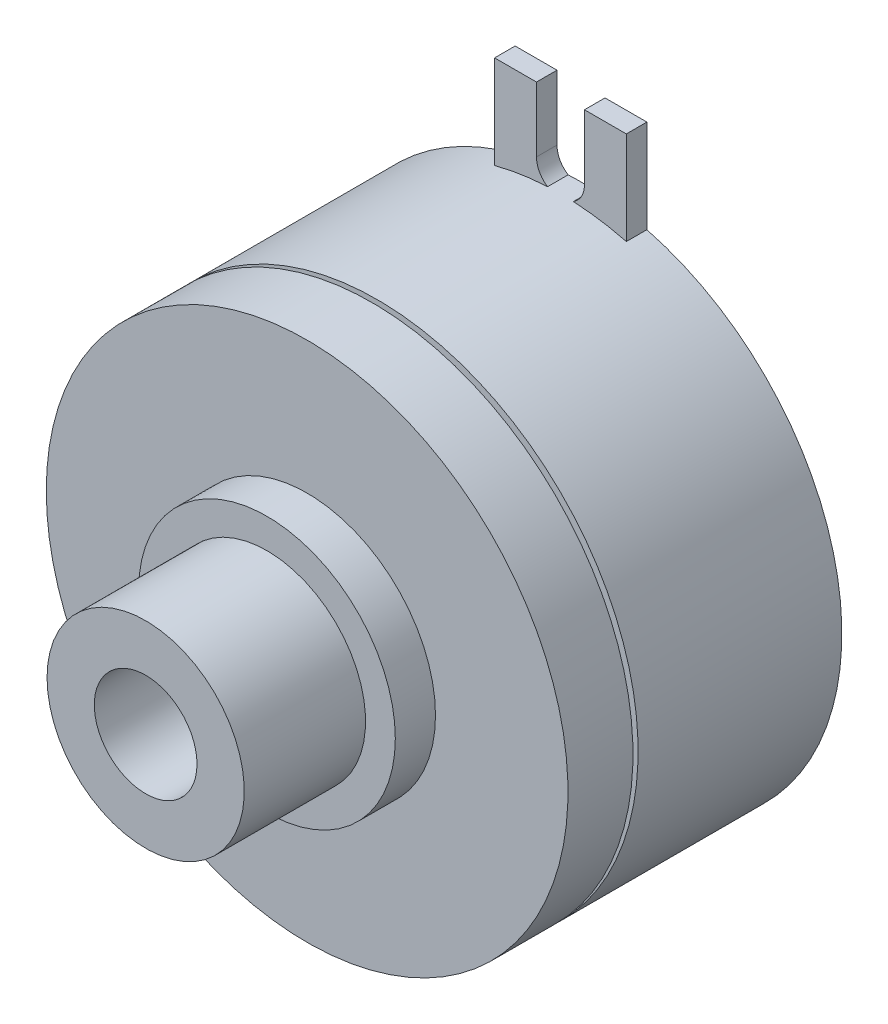
SolidWorks part; units mm, degrees
ref_plane "Front" through (0, 0, 0) normal (0, 0, 1) x (1, 0, 0)
ref_plane "Top" through (0, 0, 0) normal (0, 1, 0) x (1, 0, 0)
ref_plane "Right" through (0, 0, 0) normal (1, 0, 0) x (0, 0, -1)
sketch "Sketch1" plane through (0, 0, 0) normal (0, 0, 1) x (1, 0, 0)
  circle A0 centre (0, 0) radius 9.61
  dimension "D1" = 19.22
extrude "Boss-Extrude1" add sketch "Sketch1" along normal blind 7.087
sketch "Sketch2" plane through (0, 0, 7.087) normal (0, 0, 1) x (1, 0, 0)
  circle A0 centre (0, 0) radius 25.4
  dimension "D1" = 50.8
extrude "Boss-Extrude2" add sketch "Sketch2" along normal blind 26.67
sketch "Sketch3" plane through (0, 0, 33.757) normal (0, 0, 1) x (1, 0, 0)
  circle A0 centre (0, 0) radius 12.5
  dimension "D1" = 25
extrude "Boss-Extrude3" add sketch "Sketch3" along normal blind 3.911
sketch "Sketch4" plane through (0, 0, 37.668) normal (0, 0, 1) x (1, 0, 0)
  circle A0 centre (0, 0) radius 9.601
  dimension "D1" = 19.202
extrude "Boss-Extrude4" add sketch "Sketch4" along normal blind 11.811
sketch "Sketch6" plane through (0, 0, 7.087) normal (0, 0, -1) x (-1, 0, 0)
  line L0 (0, 36.8599) -> (0, 0) construction
  line L1 (-6.4135, 33.655) -> (-2.337, 33.655)
  line L2 (-2.337, 33.655) -> (-2.337, 27.34)
  line L4 (2.337, 27.34) -> (2.337, 33.655)
  line L5 (2.337, 33.655) -> (6.4135, 33.655)
  line L6 (6.4135, 33.655) -> (6.4135, 24.577)
  line L7 (-6.4135, 33.655) -> (-6.4135, 24.577)
  circle A0 centre (0, 0) radius 25.4 construction
  arc A1 (-2.337, 27.34) -> (2.337, 27.34) centre (0, 27.34) ccw
  circle A3 centre (0, 0) radius 9.61 construction
  circle A5 centre (0, 0) radius 25.4
  arc A6 (-6.4135, 24.577) -> (6.4135, 24.577) centre (0, 0) ccw
  dimension "D1" = 4.674
  dimension "D3" = 27.34
  dimension "D2" = 12.827
  dimension "D4" = 33.655
  dimension "D5" = 0
extrude "Boss-Extrude5" add sketch "Sketch6" against normal blind 2
sketch "Sketch5" plane through (0, 0, 49.479) normal (0, 0, 1) x (1, 0, 0)
  circle A0 centre (0, 0) radius 5
  dimension "D1" = 10
extrude "Cut-Extrude1" cut sketch "Sketch5" against normal through all
ref_plane "Plane1" through (0, 0, 26.927) normal (0, 0, -1) x (-1, 0, 0)
sketch "Sketch7" plane through (0, 0, 26.927) normal (0, 0, -1) x (-1, 0, 0)
  circle A0 centre (0, 0) radius 18.7714
extrude "Cut-Extrude2" cut sketch "Sketch7" against normal blind 0.5 flip side to cut
